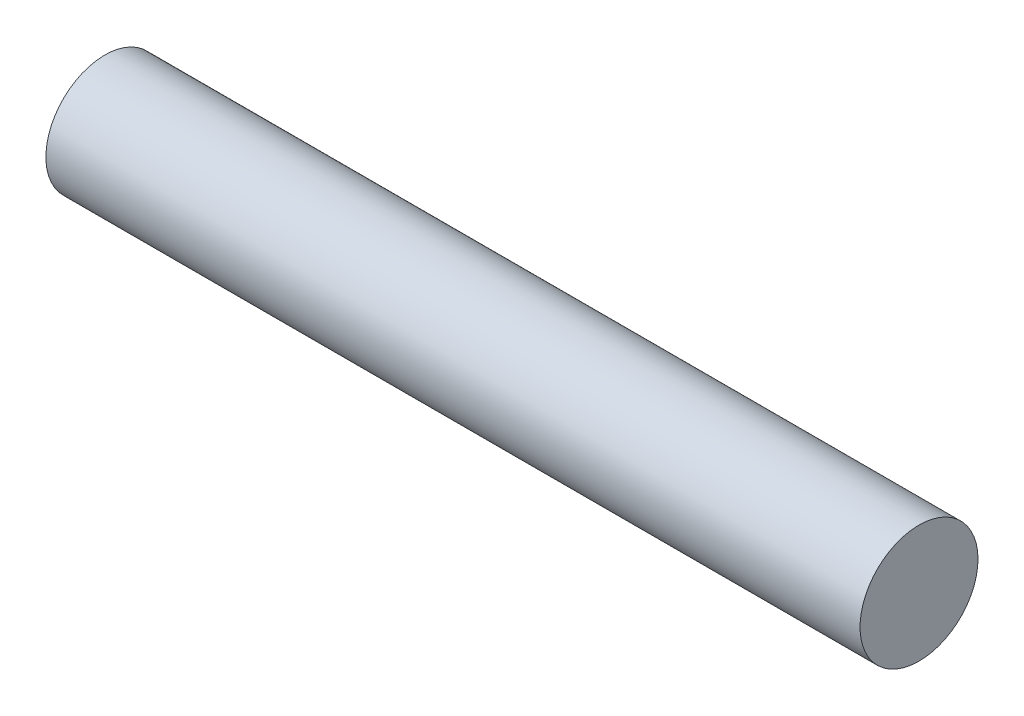
SolidWorks part; units mm, degrees
material "Stainless Steel (ferritic)"
ref_plane "Front Plane" through (0, 0, 0) normal (0, 0, 1) x (1, 0, 0)
ref_plane "Top Plane" through (0, 0, 0) normal (0, 1, 0) x (1, 0, 0)
ref_plane "Right Plane" through (0, 0, 0) normal (1, 0, 0) x (0, 0, -1)
sketch "Sketch2" plane through (0, 0, 0) normal (1, 0, 0) x (0, 0, -1)
  circle A0 centre (0, 0) radius 1.5
  dimension "D1" = 3
extrude "Boss-Extrude1" add sketch "Sketch2" along normal blind 20.71
